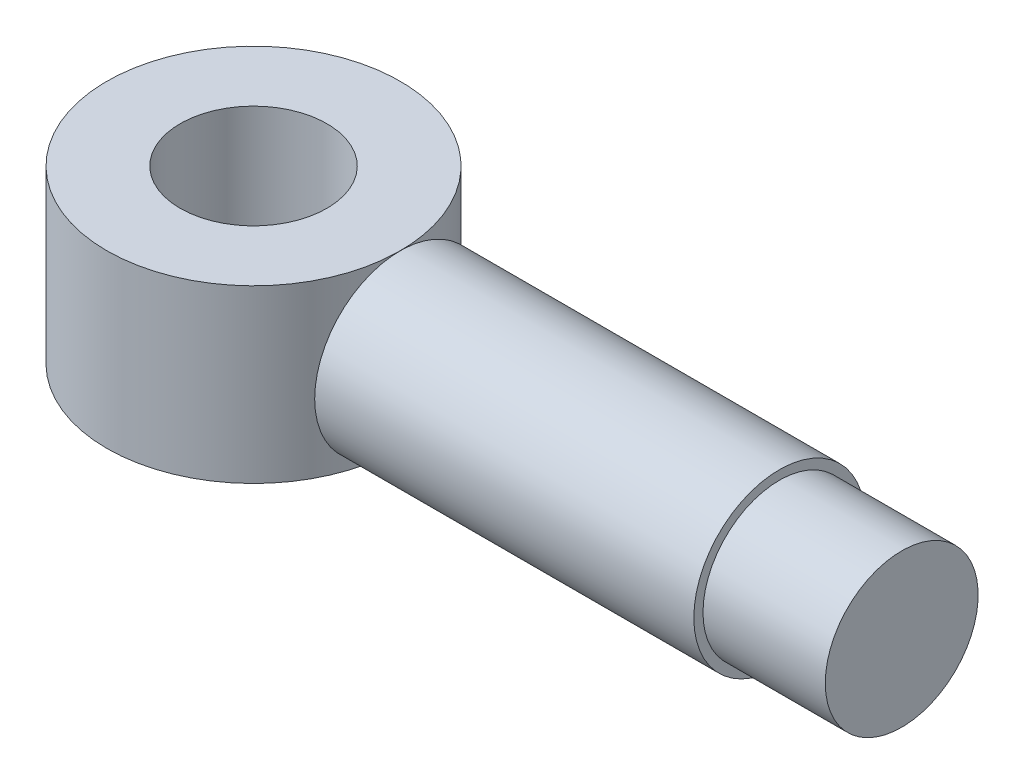
SolidWorks part; units mm, degrees
material "Stainless Steel (ferritic)"
ref_plane "Front Plane" through (0, 0, 0) normal (0, 0, 1) x (1, 0, 0)
ref_plane "Top Plane" through (0, 0, 0) normal (0, 1, 0) x (1, 0, 0)
ref_plane "Right Plane" through (0, 0, 0) normal (1, 0, 0) x (0, 0, -1)
sketch "Sketch1" plane through (0, 0, 0) normal (0, 1, 0) x (1, 0, 0)
  circle A0 centre (0, 0) radius 24
  circle A1 centre (0, 0) radius 12
  dimension "D1" = 24
  dimension "D2" = 48
extrude "Boss-Extrude1" add sketch "Sketch1" along normal blind 28
sketch "Sketch2" plane through (0, 0, 0) normal (0, 0, 1) x (1, 0, 0)
  line L0 (-976, 14) -> (49024, 14) construction
  line L1 (24, 0) -> (24, 28) construction
  line L2 (24, 14) -> (86, 14)
  line L3 (86, 14) -> (86, 28)
  line L4 (86, 28) -> (24, 28)
  line L5 (24, 28) -> (24, 14)
  line L6 (24, 28) -> (-24, 28) construction
  point P5 (24, 14)
  dimension "D1" = 86
revolve "Revolve1" add sketch "Sketch2" angle 360 about L0
sketch "Sketch3" plane through (86, 0, 0) normal (1, 0, 0) x (0, 0, -1)
  circle A0 centre (0, 14) radius 12.5
  dimension "D1" = 25
extrude "Boss-Extrude2" add sketch "Sketch3" along normal blind 20
